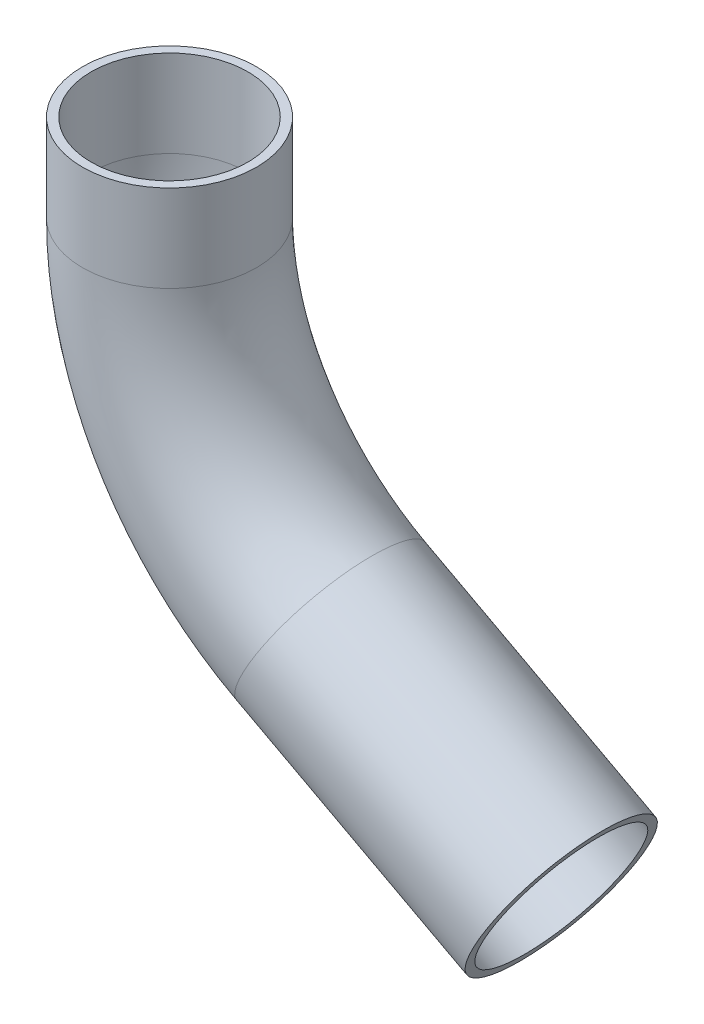
SolidWorks part; units mm, degrees
ref_plane "Front Plane" through (0, 0, 0) normal (0, 0, 1) x (1, 0, 0)
ref_plane "Top Plane" through (0, 0, 0) normal (0, 1, 0) x (1, 0, 0)
ref_plane "Right Plane" through (0, 0, 0) normal (1, 0, 0) x (0, 0, -1)
sketch "Sketch1" plane through (0, 0, 0) normal (0, 1, 0) x (1, 0, 0)
  circle A0 centre (0, 0) radius 10
  circle A1 centre (0, 0) radius 9
  dimension "D1" = 20
  dimension "D2" = 18
sketch "Sketch2" plane through (0, 0, 0) normal (0, 0, 1) x (1, 0, 0)
  line L0 (0, 0) -> (0, -10)
  line L1 (18.5294, -40.8824) -> (45, -55)
  arc A0 (0, -10) -> (18.5294, -40.8824) centre (35, -10) ccw
  dimension "D2" = 35
  dimension "D1" = 10
  dimension "D3" = 30
  dimension "D4" = 55
sweep "Sweep1" add profiles "Sketch1" path "Sketch2"
